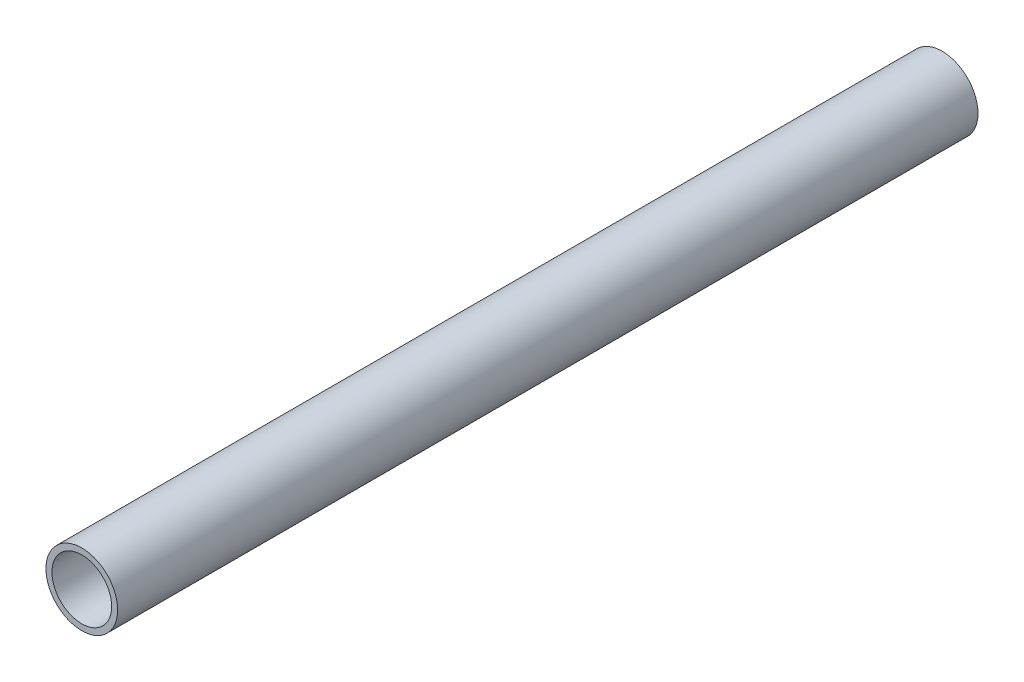
SolidWorks part; units mm, degrees
ref_plane "Front Plane" through (0, 0, 0) normal (0, 0, 1) x (1, 0, 0)
ref_plane "Top Plane" through (0, 0, 0) normal (0, 1, 0) x (1, 0, 0)
ref_plane "Right Plane" through (0, 0, 0) normal (1, 0, 0) x (0, 0, -1)
sketch "Sketch1" plane through (0, 0, 0) normal (0, 0, 1) x (1, 0, 0)
  circle A0 centre (0, 0) radius 19.05
  circle A1 centre (0, 0) radius 15.875
  dimension "D1" = 38.1
  dimension "D2" = 31.75
extrude "Boss-Extrude1" add sketch "Sketch1" along normal blind 457.2
